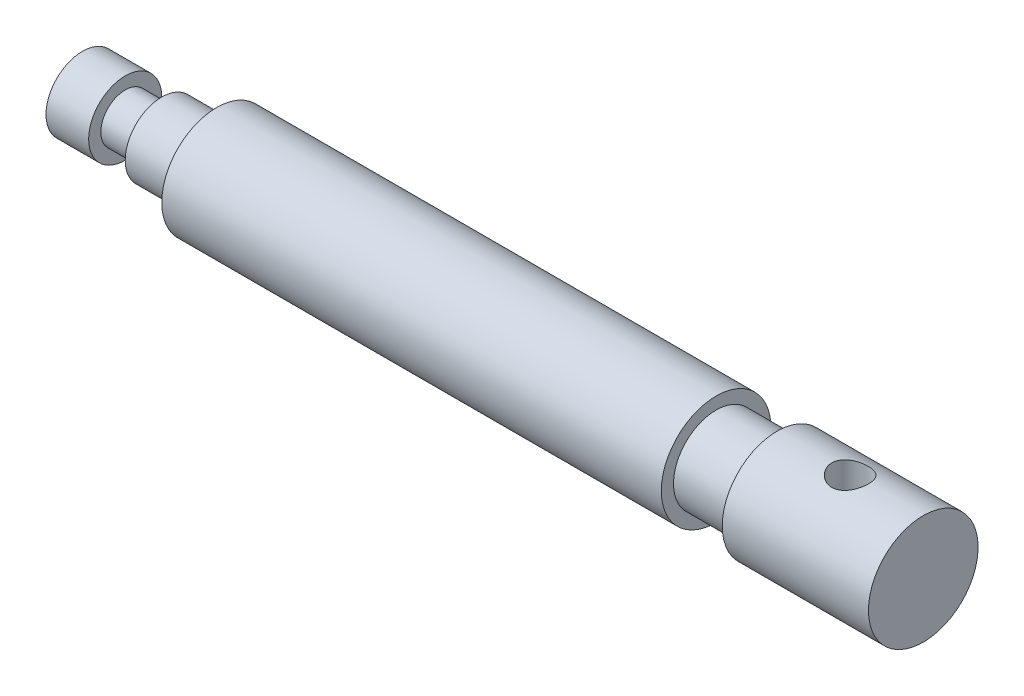
SolidWorks part; units mm, degrees
ref_plane "Front Plane" through (0, 0, 0) normal (0, 0, 1) x (1, 0, 0)
ref_plane "Top Plane" through (0, 0, 0) normal (0, 1, 0) x (1, 0, 0)
ref_plane "Right Plane" through (0, 0, 0) normal (1, 0, 0) x (0, 0, -1)
sketch "Sketch1" plane through (0, 0, 0) normal (0, 1, 0) x (1, 0, 0)
  line L0 (0, 0) -> (138, 0) construction
  line L1 (0, 0) -> (0, 6)
  line L2 (0, 6) -> (7, 6)
  line L3 (7, 6) -> (7, 4)
  line L4 (7, 4) -> (13, 4)
  line L5 (13, 4) -> (13, 6)
  line L6 (138, 9) -> (138, 0)
  line L7 (138, 9) -> (114, 9)
  line L8 (114, 9) -> (114, 7)
  line L9 (138, 0) -> (0, 0)
  line L10 (114, 7) -> (104, 7)
  line L11 (104, 7) -> (104, 9)
  line L12 (104, 9) -> (22, 9)
  line L13 (13, 6) -> (22, 6)
  line L14 (22, 6) -> (22, 9)
revolve "Revolve1" add sketch "Sketch1" angle 360 about L0
sketch "Sketch3" plane through (0, 0, 0) normal (0, 1, 0) x (1, 0, 0)
  circle A0 centre (126, 0) radius 3
extrude "Cut-Extrude3" cut sketch "Sketch3" along normal through all both and the other way through all
